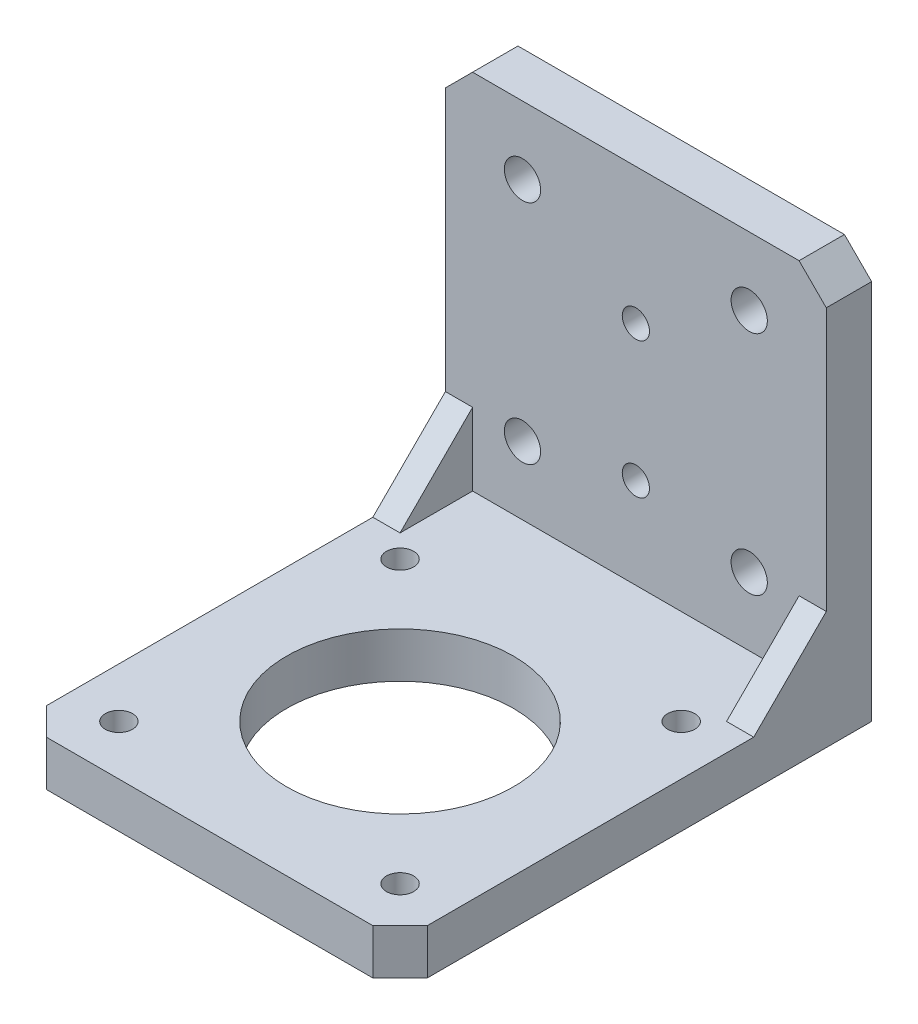
SolidWorks part; units mm, degrees
ref_plane "Front Plane" through (0, 0, 0) normal (0, 0, 1) x (1, 0, 0)
ref_plane "Top Plane" through (0, 0, 0) normal (0, 1, 0) x (1, 0, 0)
ref_plane "Right Plane" through (0, 0, 0) normal (1, 0, 0) x (0, 0, -1)
sketch "Sketch1" plane through (0, 0, 0) normal (0, 1, 0) x (1, 0, 0)
  line L1 (-21, -23.5) -> (21, -23.5)
  line L2 (-21, -23.5) -> (-21, 23.5)
  line L3 (-21, 23.5) -> (21, 23.5)
  line L4 (21, -23.5) -> (21, 23.5)
  line L5 (-21, -23.5) -> (21, 23.5) construction
  line L6 (-21, 23.5) -> (21, -23.5) construction
  point P0 (0, 0)
  dimension "D1" = 47
  dimension "D2" = 42
extrude "Boss-Extrude1" add sketch "Sketch1" along normal blind 5
sketch "Sketch2" plane through (0, 5, 0) normal (0, 1, 0) x (1, 0, 0)
  line L0 (0, 23.5) -> (0, -23.5) construction
  line L1 (-15.5, -18) -> (15.5, -18) construction
  line L2 (-15.5, -18) -> (-15.5, 13) construction
  line L3 (-15.5, 13) -> (15.5, 13) construction
  line L4 (15.5, -18) -> (15.5, 13) construction
  line L5 (-15.5, -18) -> (15.5, 13) construction
  line L6 (-15.5, 13) -> (15.5, -18) construction
  line L7 (21, 23.5) -> (-21, 23.5) construction
  line L8 (-21, -23.5) -> (21, -23.5) construction
  circle A0 centre (-15.5, 13) radius 1.5
  circle A1 centre (15.5, 13) radius 1.5
  circle A2 centre (15.5, -18) radius 1.5
  circle A3 centre (-15.5, -18) radius 1.5
  circle A4 centre (0, -2.5) radius 12.5
  point P0 (0, -2.5)
  dimension "D2" = 3
  dimension "D3" = 25
  dimension "D1" = 31
  dimension "D4" = 21
extrude "Cut-Extrude1" cut sketch "Sketch2" against normal through all
sketch "Sketch4" plane through (0, 0, -23.5) normal (0, 0, -1) x (-1, 0, 0)
  line L0 (21, 5) -> (21, 0) construction
  line L1 (-21, 0) -> (21, 0)
  line L2 (-21, 0) -> (-21, 45)
  line L3 (-21, 45) -> (21, 45)
  line L4 (21, 0) -> (21, 45)
  line L5 (-21, 5) -> (21, 5) construction
  dimension "D1" = 40
extrude "Boss-Extrude2" add sketch "Sketch4" along normal blind 5
sketch "Sketch5" plane through (21, 0, 0) normal (1, 0, 0) x (0, 0, -1)
  line L0 (23.5, 13) -> (15.5, 5)
  line L1 (23.5, 45) -> (23.5, 5) construction
  line L2 (-23.5, 5) -> (23.5, 5) construction
  line L3 (15.5, 5) -> (23.5, 5)
  line L4 (23.5, 5) -> (23.5, 13)
  dimension "D1" = 8
extrude "Boss-Extrude3" add sketch "Sketch5" against normal blind 3
sketch "Sketch6" plane through (-21, 0, 0) normal (-1, 0, 0) x (0, 0, 1)
  line L0 (-23.5, 13) -> (-15.5, 5)
  line L1 (-23.5, 5) -> (-23.5, 45) construction
  line L2 (-23.5, 5) -> (23.5, 5) construction
  line L3 (-15.5, 5) -> (-23.5, 5)
  line L4 (-23.5, 5) -> (-23.5, 13)
  dimension "D1" = 8
extrude "Boss-Extrude4" add sketch "Sketch6" against normal blind 3
sketch "Sketch9" plane through (0, 0, -23.5) normal (0, 0, 1) x (1, 0, 0)
  line L0 (0, 45) -> (0, 5) construction
  line L1 (-21, 45) -> (21, 45) construction
  line L2 (18, 5) -> (-18, 5) construction
  line L4 (-12.5, 12.5) -> (12.5, 12.5) construction
  line L5 (-12.5, 12.5) -> (-12.5, 37.5) construction
  line L6 (-12.5, 37.5) -> (12.5, 37.5) construction
  line L7 (12.5, 12.5) -> (12.5, 37.5) construction
  line L8 (-12.5, 12.5) -> (12.5, 37.5) construction
  line L9 (-12.5, 37.5) -> (12.5, 12.5) construction
  circle A0 centre (-12.5, 37.5) radius 2
  circle A1 centre (12.5, 37.5) radius 2
  circle A2 centre (12.5, 12.5) radius 2
  circle A3 centre (-12.5, 12.5) radius 2
  point P6 (0, 25)
  dimension "D1" = 4
  dimension "D2" = 25
  dimension "D3" = 25
extrude "Cut-Extrude4" cut sketch "Sketch9" against normal through all
chamfer "Chamfer3" distance 3 angle 45 4 edges at (-21, 2.5, 23.5) (21, 2.5, 23.5) (21, 45, -26) (-21, 45, -26)
sketch "Sketch10" plane through (0, 0, -28.5) normal (0, 0, -1) x (-1, 0, 0)
  circle A0 centre (0, 30) radius 1.5 construction
  circle A1 centre (0, 30) radius 1.5
  circle A2 centre (0, 15) radius 1.5 construction
  circle A3 centre (0, 15) radius 1.5
extrude "Cut-Extrude5" cut sketch "Sketch10" against normal up to next
